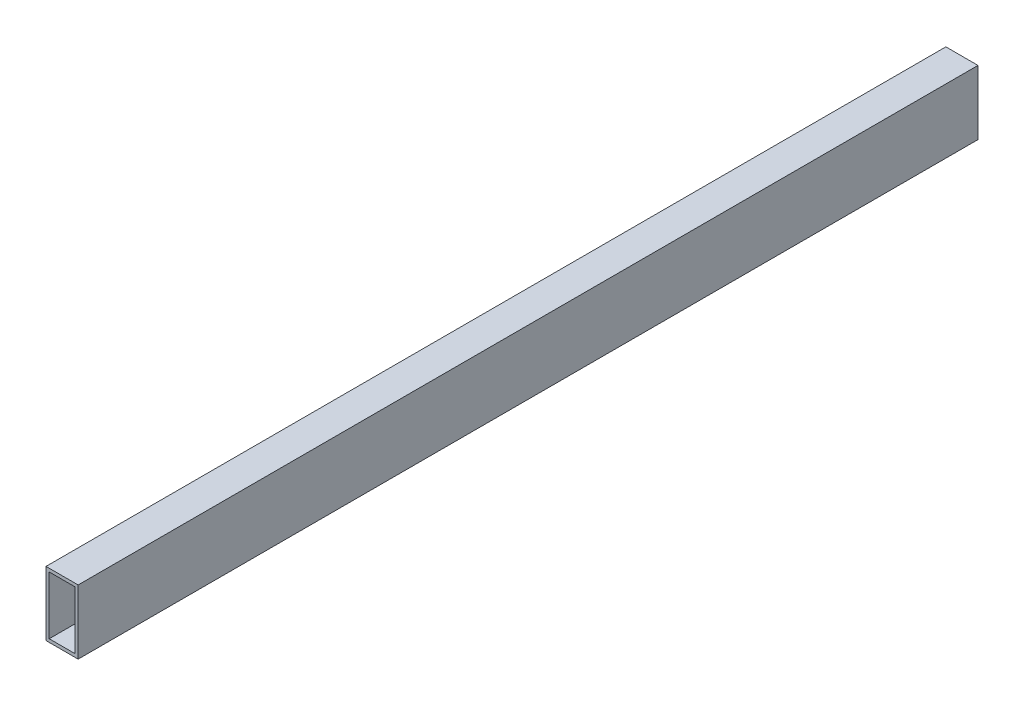
SolidWorks part; units mm, degrees
ref_plane "Front Plane" through (0, 0, 0) normal (0, 0, 1) x (1, 0, 0)
ref_plane "Top Plane" through (0, 0, 0) normal (0, 1, 0) x (1, 0, 0)
ref_plane "Right Plane" through (0, 0, 0) normal (1, 0, 0) x (0, 0, -1)
sketch "Sketch1" plane through (0, 0, 0) normal (0, 0, 1) x (1, 0, 0)
  line L0 (-4, 9) -> (4, 9)
  line L1 (-5, -10) -> (5, -10)
  line L2 (-5, -10) -> (-5, 10)
  line L3 (-5, 10) -> (5, 10)
  line L4 (5, -10) -> (5, 10)
  line L5 (-5, -10) -> (5, 10) construction
  line L6 (-5, 10) -> (5, -10) construction
  line L7 (4, -9) -> (4, 9)
  line L8 (-4, -9) -> (4, -9)
  line L9 (-4, -9) -> (-4, 9)
  point P0 (0, 0)
  dimension "D1" = 10
  dimension "D2" = 20
  dimension "D3" = 1
extrude "Boss-Extrude1" add sketch "Sketch1" along normal blind 280
